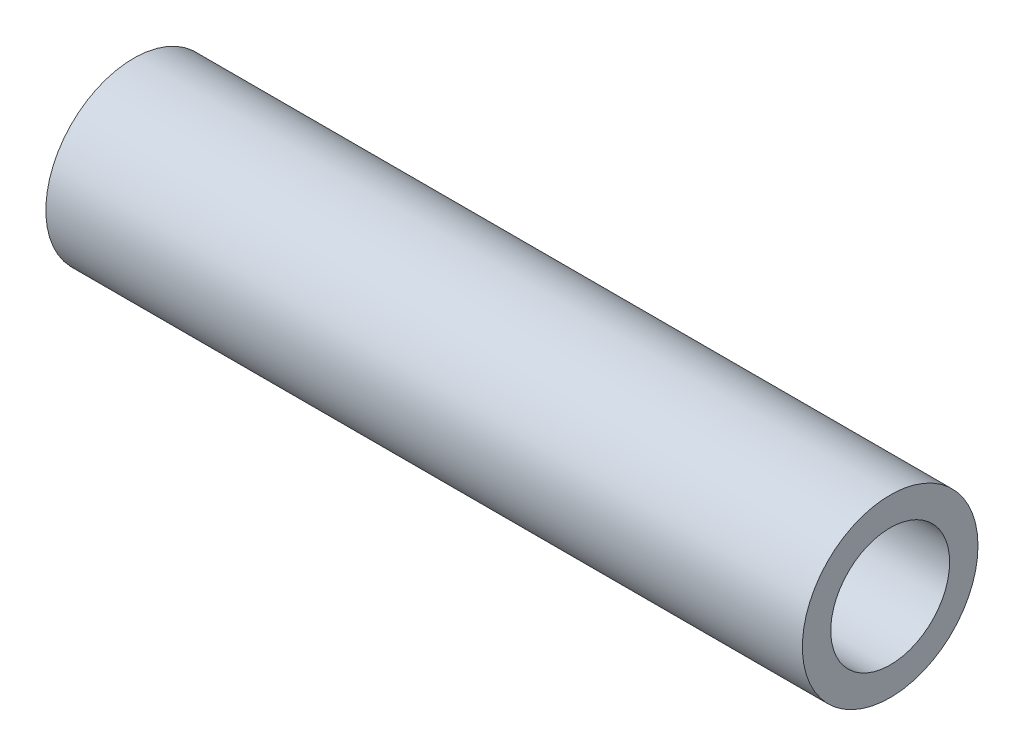
SolidWorks part; units mm, degrees
ref_plane "Front Plane" through (0, 0, 0) normal (0, 0, 1) x (1, 0, 0)
ref_plane "Top Plane" through (0, 0, 0) normal (0, 1, 0) x (1, 0, 0)
ref_plane "Right Plane" through (0, 0, 0) normal (1, 0, 0) x (0, 0, -1)
sketch "Sketch1" plane through (0, 0, 0) normal (1, 0, 0) x (0, 0, -1)
  circle A0 centre (0, 0) radius 2 construction
  circle A1 centre (0, 0) radius 3.45 construction
  circle A2 centre (0, 0) radius 3.25
  circle A3 centre (0, 0) radius 2.2
  dimension "D3" = 4
  dimension "D4" = 6.5
  dimension "D1" = 0.2
  dimension "D2" = 0.2
extrude "Boss-Extrude1" add sketch "Sketch1" along normal blind 28
equation "\"Tolerance\"= 0.2"
equation "\"D1@Sketch1\"=\"Tolerance\""
equation "\"D2@Sketch1\"=\"Tolerance\""
